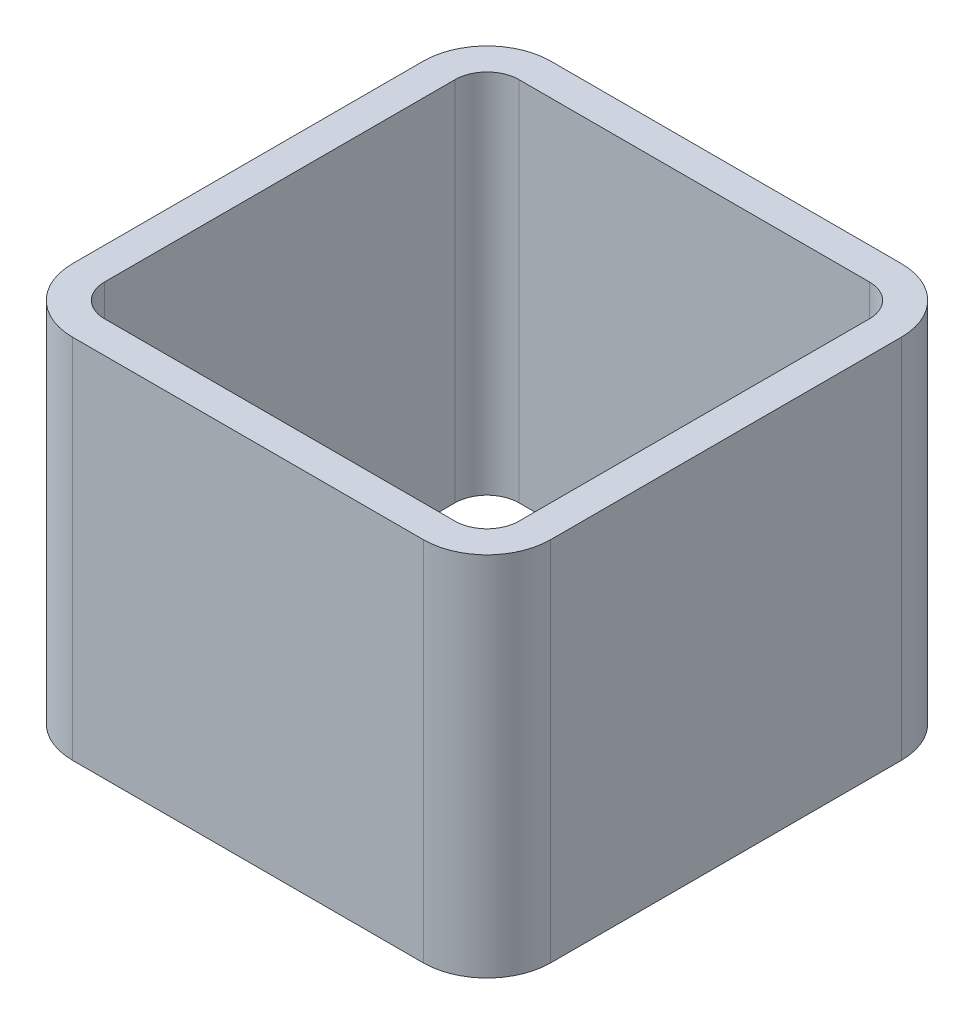
SolidWorks part; units mm, degrees
material "AISI 1010 钢，热轧条材"
ref_plane "前视基准面" through (0, 0, 0) normal (0, 0, 1) x (1, 0, 0)
ref_plane "上视基准面" through (0, 0, 0) normal (0, 1, 0) x (1, 0, 0)
ref_plane "右视基准面" through (0, 0, 0) normal (1, 0, 0) x (0, 0, -1)
sketch "草图1" plane through (0, 0, 0) normal (0, 1, 0) x (1, 0, 0)
  line L0 (-11, -13) -> (11, -13)
  line L1 (-11, -15) -> (11, -15)
  line L2 (-15, -11) -> (-15, 11)
  line L3 (-11, 15) -> (11, 15)
  line L4 (15, -11) -> (15, 11)
  line L5 (13, -11) -> (13, 11)
  line L6 (-11, 13) -> (11, 13)
  line L7 (-13, -11) -> (-13, 11)
  arc A0 (-11, -15) -> (-15, -11) centre (-11, -11) cw
  arc A1 (11, -15) -> (15, -11) centre (11, -11) ccw
  arc A2 (11, 15) -> (15, 11) centre (11, 11) cw
  arc A3 (-15, 11) -> (-11, 15) centre (-11, 11) cw
  arc A4 (11, -13) -> (13, -11) centre (11, -11) ccw
  arc A5 (11, 13) -> (13, 11) centre (11, 11) cw
  arc A6 (-13, 11) -> (-11, 13) centre (-11, 11) cw
  arc A7 (-11, -13) -> (-13, -11) centre (-11, -11) cw
  point P7 (-15, -15)
  point P10 (15, -15)
  point P13 (15, 15)
  point P16 (-15, 15)
  dimension "D3" = 4
  dimension "D1" = 30
  dimension "D2" = 30
  dimension "D4" = 2
extrude "凸台-拉伸1" add sketch "草图1" along normal mid plane 23
